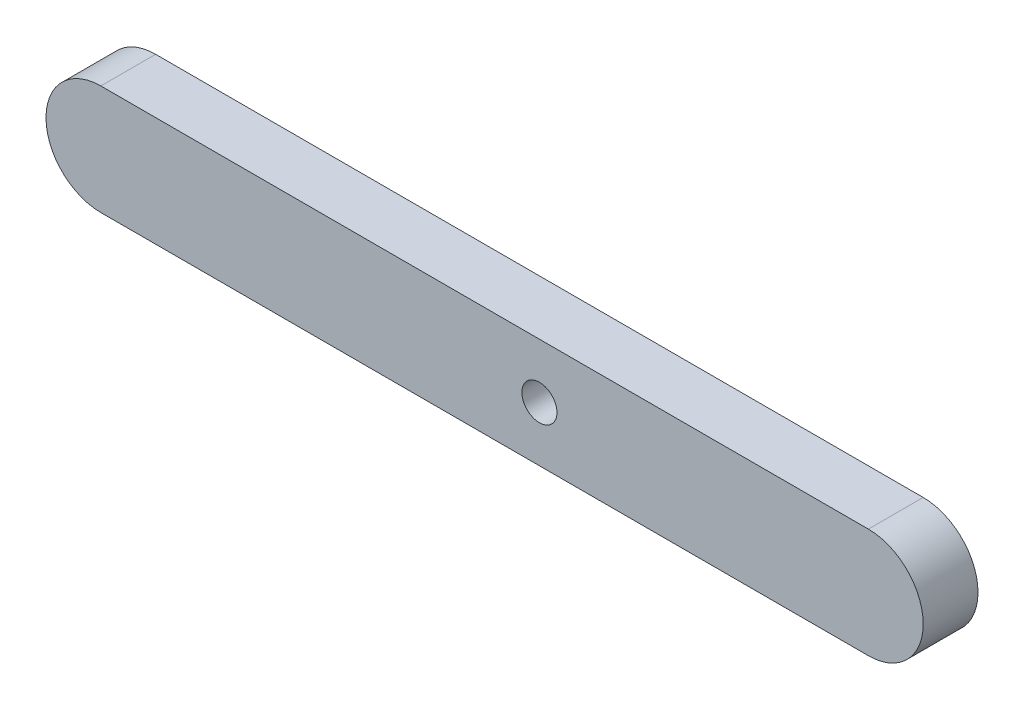
SolidWorks part; units mm, degrees
ref_plane "前视基准面" through (0, 0, 0) normal (0, 0, 1) x (1, 0, 0)
ref_plane "上视基准面" through (0, 0, 0) normal (0, 1, 0) x (1, 0, 0)
ref_plane "右视基准面" through (0, 0, 0) normal (1, 0, 0) x (0, 0, -1)
other "Configuration Table"
sketch "草图1" plane through (0, 0, 0) normal (0, 0, 1) x (1, 0, 0)
  line L0 (0, 0) -> (70, 0) construction
  line L1 (0, 5) -> (70, 5)
  line L2 (0, -5) -> (70, -5)
  arc A0 (0, 5) -> (0, -5) centre (0, 0) ccw
  arc A1 (70, -5) -> (70, 5) centre (70, 0) ccw
  circle A2 centre (40, 0) radius 1.6
  point P3 (35, 0)
  dimension "D4" = 3.2
  dimension "D1" = 70
  dimension "D2" = 10
  dimension "D3" = 40
extrude "凸台-拉伸1" add sketch "草图1" along normal blind 5
